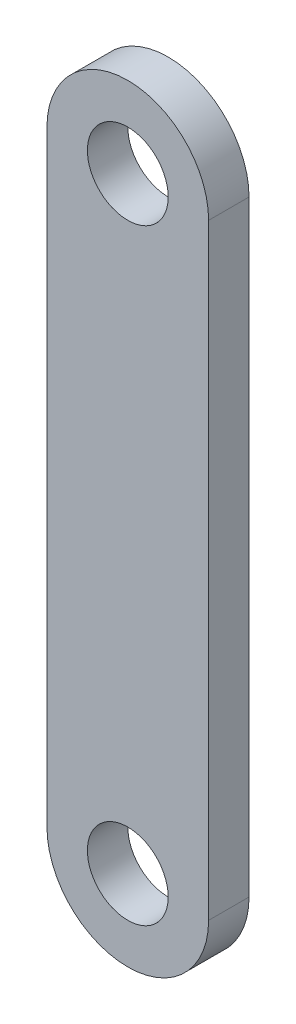
SolidWorks part; units mm, degrees
ref_plane "Front Plane" through (0, 0, 0) normal (0, 0, 1) x (1, 0, 0)
ref_plane "Top Plane" through (0, 0, 0) normal (0, 1, 0) x (1, 0, 0)
ref_plane "Right Plane" through (0, 0, 0) normal (1, 0, 0) x (0, 0, -1)
sketch "Sketch1" plane through (0, 0, 0) normal (0, 0, 1) x (1, 0, 0)
  line L0 (0, -9.525) -> (0, 9.525) construction
  line L1 (-2.54, -9.525) -> (-2.54, 9.525)
  line L2 (2.54, -9.525) -> (2.54, 9.525)
  arc A0 (-2.54, -9.525) -> (2.54, -9.525) centre (0, -9.525) ccw
  arc A1 (2.54, 9.525) -> (-2.54, 9.525) centre (0, 9.525) ccw
  point P2 (0, 0)
  dimension "D2" = 2.54
  dimension "D1" = 19.05
extrude "body" add sketch "Sketch1" along normal blind 1.27
sketch "Sketch2" plane through (0, 0, 1.27) normal (0, 0, 1) x (1, 0, 0)
  circle A0 centre (0, 9.525) radius 1.27
  circle A1 centre (0, -9.525) radius 1.27
  dimension "D1" = 2.54
  dimension "D2" = 2.54
extrude "linkage holes" cut sketch "Sketch2" against normal blind 2.54
